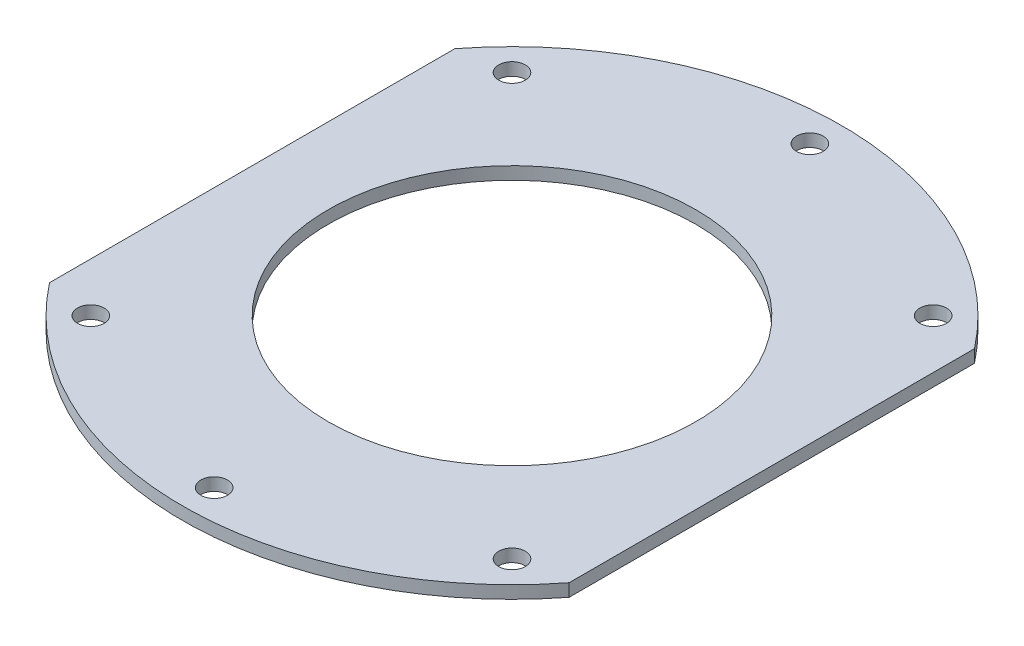
SolidWorks part; units mm, degrees
ref_plane "前视基准面" through (0, 0, 0) normal (0, 0, 1) x (1, 0, 0)
ref_plane "上视基准面" through (0, 0, 0) normal (0, 1, 0) x (1, 0, 0)
ref_plane "右视基准面" through (0, 0, 0) normal (1, 0, 0) x (0, 0, -1)
sketch "草图1" plane through (0, 0, 0) normal (0, 1, 0) x (1, 0, 0)
  circle A0 centre (0, 0) radius 29
  circle A1 centre (0, 0) radius 52
  circle A2 centre (47, 0) radius 2.1
  circle A3 centre (33.234, -33.234) radius 2.1
  circle A4 centre (0, -47) radius 2.1
  circle A5 centre (-33.234, -33.234) radius 2.1
  circle A6 centre (-47, 0) radius 2.1
  circle A7 centre (-33.234, 33.234) radius 2.1
  circle A8 centre (0, 47) radius 2.1
  circle A9 centre (33.234, 33.234) radius 2.1
  circle A10 centre (0, 0) radius 43 construction
  point P6 (52, 0)
  point P9 (43, 0)
  dimension "D1" = 58
  dimension "D2" = 86
  dimension "D3" = 4
  dimension "D4" = 4.2
  dimension "D7" = 5
  dimension "D5" = 8
extrude "凸台-拉伸1" add sketch "草图1" along normal blind 2
sketch "草图2" plane through (0, 2, 0) normal (0, 1, 0) x (1, 0, 0)
  line L1 (-41, -55.0176) -> (41, -55.0176)
  line L2 (-41, -55.0176) -> (-41, 55.0176)
  line L3 (-41, 55.0176) -> (41, 55.0176)
  line L4 (41, -55.0176) -> (41, 55.0176)
  line L5 (-41, -55.0176) -> (41, 55.0176) construction
  line L6 (-41, 55.0176) -> (41, -55.0176) construction
  point P0 (0, 0)
  dimension "D1" = 82
extrude "切除-拉伸-薄壁1" cut sketch "草图2" against normal blind 10 thin
